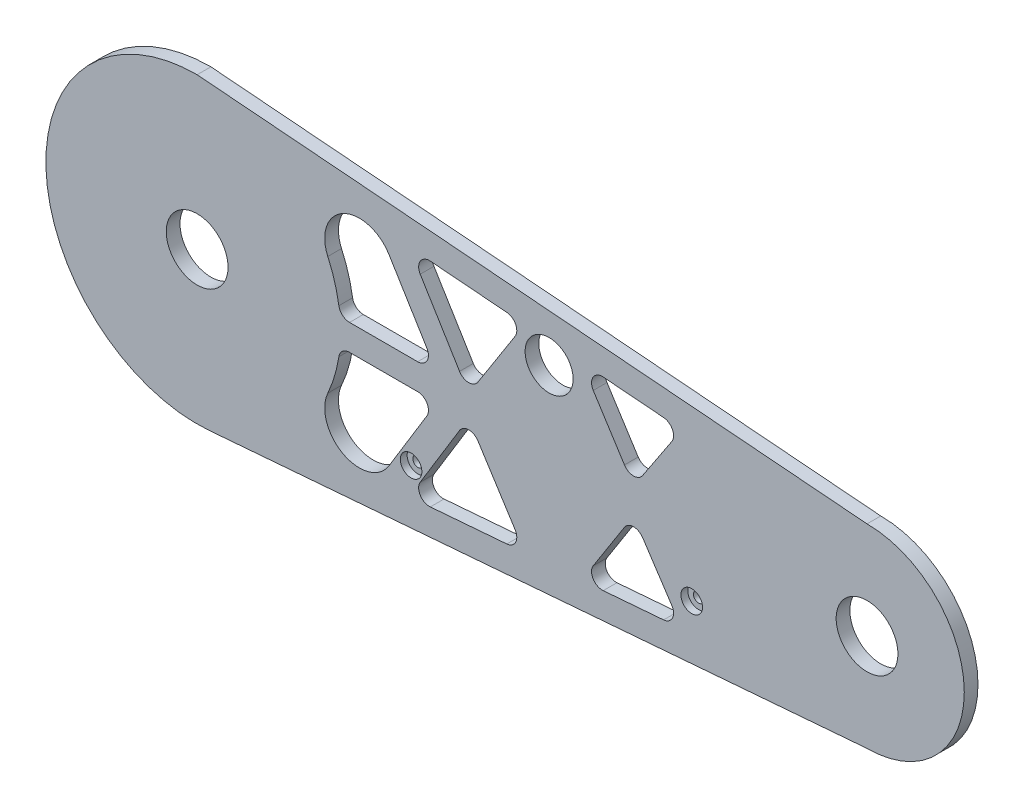
SolidWorks part; units mm, degrees
other "Marca1"
sketch "Croquis3" plane through (-70, -70, 6.35) normal (0, 0, 1) x (1, 0, 0)
material "6061-O (SS)"
ref_plane "Front Plane" through (0, 0, 0) normal (0, 0, 1) x (1, 0, 0)
ref_plane "Top Plane" through (0, 0, 0) normal (0, 1, 0) x (1, 0, 0)
ref_plane "Right Plane" through (0, 0, 0) normal (1, 0, 0) x (0, 0, -1)
sketch "Sketch1" plane through (0, 0, 0) normal (0, 0, 1) x (1, 0, 0)
  line L0 (0, 70) -> (310, 45)
  line L1 (5.1714, -69.8087) -> (310, -45)
  line L2 (0, 0) -> (310, 0) construction
  line L3 (107.899, 49.2595) -> (143.3142, 46.4034)
  line L4 (70.5232, 6) -> (102.03, 6)
  line L5 (219.6238, 32.8105) -> (206.1309, 12.4175)
  line L6 (197.7459, 12.4871) -> (183.2969, 35.1335)
  line L7 (162.8785, 6) -> (162.8785, -6) construction
  line L8 (258.6323, 64.5867) -> (258.6323, 39.5867) construction
  line L9 (147.1275, 38.7303) -> (129.9162, 11.7546)
  line L10 (121.433, 11.8395) -> (103.229, 41.6712)
  line L11 (98.117, 50.0484) -> (42.0027, 50.0484) construction
  line L12 (187.9139, 42.8067) -> (215.8558, 40.5533)
  line L13 (162.8785, 44.8257) -> (162.8785, 6) construction
  line L14 (67.1248, 64.5867) -> (162.8785, 35) construction
  line L15 (201.8849, 6) -> (201.8849, 41.68) construction
  line L16 (125.6066, 5) -> (125.6066, 47.8315) construction
  line L17 (88.7465, 42.3671) -> (106.2981, 13.6045)
  line L18 (125.6066, -5) -> (125.6066, -47.8315) construction
  line L19 (201.8849, -6) -> (201.8849, -41.68) construction
  line L20 (162.8785, -44.8257) -> (162.8785, -6) construction
  line L21 (98.117, -50.0484) -> (42.0027, -50.0484) construction
  line L22 (88.7465, -42.3671) -> (106.2981, -13.6045)
  line L23 (67.1248, 64.5867) -> (409.6974, 64.5867) construction
  line L24 (187.9139, -42.8067) -> (215.8558, -40.5533)
  line L25 (121.433, -11.8395) -> (103.229, -41.6712)
  line L26 (147.1275, -38.7303) -> (129.9162, -11.7546)
  line L27 (162.8785, 0) -> (258.6323, 64.5867) construction
  line L28 (67.1248, 64.5867) -> (67.1248, 39.5867) construction
  line L29 (197.7459, -12.4871) -> (183.2969, -35.1335)
  line L30 (219.6238, -32.8105) -> (206.1309, -12.4175)
  line L31 (70.5232, -6) -> (102.03, -6)
  line L32 (107.899, -49.2595) -> (143.3142, -46.4034)
  line L33 (0, -6.35) -> (0, 6.35) construction
  line L34 (67.1248, 39.5867) -> (162.8785, 35) construction
  line L35 (162.8785, 35) -> (67.6719, 24.0904) construction
  arc A0 (65.583, 10.2294) -> (70.5232, 6) centre (70.5232, 11) ccw
  arc A1 (310, -45) -> (310, 45) centre (310, 0) ccw
  circle A2 centre (0, 0) radius 14.2938
  circle A3 centre (310, 0) radius 14.2939
  arc A4 (60.4576, 27.3979) -> (88.7465, 42.3671) centre (75.0607, 34.0157) cw
  arc A5 (60.4576, -27.3979) -> (65.583, -10.2294) centre (0, 0) ccw
  arc A6 (0, 70) -> (5.1714, -69.8087) centre (0, 0) ccw
  arc A7 (187.9139, 42.8067) -> (183.2969, 35.1335) centre (187.512, 37.8229) ccw
  arc A8 (219.6238, 32.8105) -> (215.8558, 40.5533) centre (215.4539, 35.5695) ccw
  arc A9 (206.1309, 12.4175) -> (197.7459, 12.4871) centre (201.961, 15.1765) cw
  circle A10 centre (162.8785, 35) radius 11.1125
  arc A13 (102.03, 6) -> (106.2981, 13.6045) centre (102.03, 11) ccw
  arc A14 (121.433, 11.8395) -> (129.9162, 11.7546) centre (125.7011, 14.444) ccw
  arc A15 (147.1275, 38.7303) -> (143.3142, 46.4034) centre (142.9123, 41.4196) ccw
  arc A16 (107.899, 49.2595) -> (103.229, 41.6712) centre (107.4971, 44.2757) ccw
  arc A17 (107.899, -49.2595) -> (103.229, -41.6712) centre (107.4971, -44.2757) cw
  arc A18 (147.1275, -38.7303) -> (143.3142, -46.4034) centre (142.9123, -41.4196) cw
  arc A19 (121.433, -11.8395) -> (129.9162, -11.7546) centre (125.7011, -14.444) cw
  arc A20 (102.03, -6) -> (106.2981, -13.6045) centre (102.03, -11) cw
  arc A24 (206.1309, -12.4175) -> (197.7459, -12.4871) centre (201.961, -15.1765) ccw
  arc A25 (219.6238, -32.8105) -> (215.8558, -40.5533) centre (215.4539, -35.5695) cw
  arc A26 (187.9139, -42.8067) -> (183.2969, -35.1335) centre (187.512, -37.8229) cw
  arc A27 (65.583, 10.2294) -> (60.4576, 27.3979) centre (0, 0) ccw
  arc A28 (60.4576, -27.3979) -> (88.7465, -42.3671) centre (75.0607, -34.0157) ccw
  arc A29 (65.583, -10.2294) -> (70.5232, -6) centre (70.5232, -11) cw
  point P31 (177.8851, 43.6155)
  point P42 (187.6504, 6)
  point P45 (138.1067, 6)
  point P100 (138.1067, -6)
  point P101 (187.6504, -6)
  point P102 (177.8851, -43.6155)
  point P104 (0, 0)
  point P114 (310, 0)
  point P119 (0.2114, 0.3175)
  dimension "D2" = 45
  dimension "D3" = 12.7
  dimension "D4" = 28.5877
  dimension "D6" = 12
  dimension "D11" = 5
  dimension "D12" = 70
  dimension "D13" = 25
  dimension "D8" = 5
  dimension "D14" = 12
  dimension "D15" = 25
  dimension "D16" = 310
  dimension "D17" = 22.225
  dimension "D5" = 28.5877
  dimension "D7" = 6
  dimension "D9" = 9.279
  dimension "D10" = 34
  dimension "D18" = 35
extrude "Boss-Extrude1" add sketch "Sketch1" along normal blind 6.35
sketch "Sketch2" plane through (0, 0, 6.35) normal (0, 0, 1) x (1, 0, 0)
  line L0 (263.0927, 39.4927) -> (-0.4655, 64.9983)
  line L1 (4.6885, -64.8307) -> (263.1366, -39.5384)
  arc A0 (-0.4655, 64.9983) -> (4.6885, -64.8307) centre (0, 0) ccw
  arc A1 (263.1366, -39.5384) -> (270.3186, -23.7999) centre (262.1626, -29.5859) ccw
  circle A2 centre (0, 0) radius 40
  arc A3 (270.292, 23.7623) -> (270.3186, -23.7999) centre (303.867, 0) ccw
  arc A4 (270.292, 23.7623) -> (263.0927, 39.4927) centre (262.1295, 29.5392) ccw
  dimension "D1" = 10
  dimension "D2" = 41.133
  dimension "D3" = 65
ref_plane "Plane1" through (0, 0, 10) normal (0, 0, 1) x (1, 0, 0)
sketch "Croquis1" plane through (0, 0, 6.35) normal (0, 0, 1) x (1, 0, 0)
  line L0 (5.1714, -69.8087) -> (310, -45) construction
  line L1 (310, -45) -> (307.9721, -20.0824) construction
  line L3 (3.1435, -44.8911) -> (307.9721, -20.0824) construction
  line L9 (100.6836, -22.8053) -> (88.7465, -42.3671) construction
  line L10 (88.7465, -42.3671) -> (106.2981, -13.6045) construction
  circle A1 centre (98.9956, -37.0901) radius 2.3813
  circle A2 centre (228.8774, -26.5196) radius 2.3813
  point P0 (0, 0)
  point P12 (70, 0)
  point P20 (0, 0)
  dimension "D5" = 4.7625
  dimension "D1" = 4.7625
  dimension "D4" = 6
extrude "Cortar-Extruir1" cut sketch "Croquis1" against normal blind 50
sketch "Croquis2" plane through (0, 0, 6.35) normal (0, 0, 1) x (1, 0, 0)
  circle A0 centre (98.9956, -37.0901) radius 5
  circle A1 centre (228.8774, -26.5196) radius 5
  dimension "D1" = 10
extrude "Cortar-Extruir2" cut sketch "Croquis2" against normal blind 3.175
